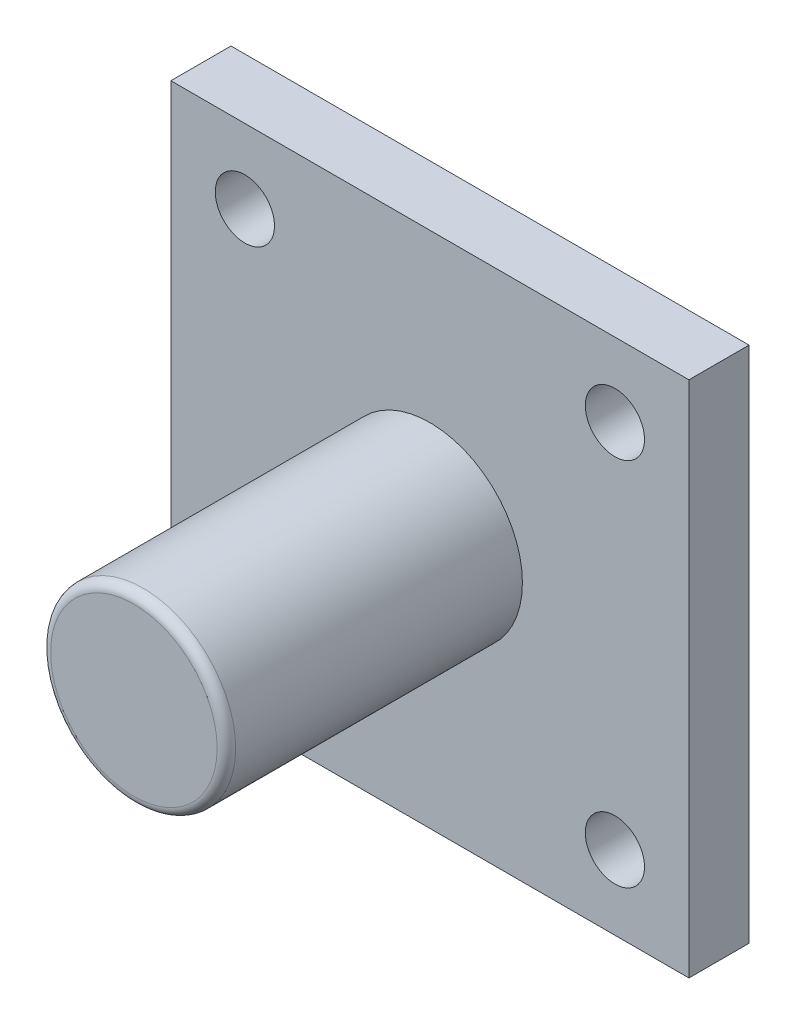
SolidWorks part; units mm, degrees
ref_plane "Front Plane" through (0, 0, 0) normal (0, 0, 1) x (1, 0, 0)
ref_plane "Top Plane" through (0, 0, 0) normal (0, 1, 0) x (1, 0, 0)
ref_plane "Right Plane" through (0, 0, 0) normal (1, 0, 0) x (0, 0, -1)
sketch "Sketch1" plane through (0, 0, 0) normal (0, 0, 1) x (1, 0, 0)
  line L1 (0, 0) -> (28, 0)
  line L2 (0, 0) -> (0, 28)
  line L3 (0, 28) -> (28, 28)
  line L4 (28, 0) -> (28, 28)
  dimension "D1" = 28
  dimension "D2" = 28
extrude "Boss-Extrude1" add sketch "Sketch1" along normal blind 3.25
sketch "Sketch2" plane through (0, 0, 3.25) normal (0, 0, 1) x (1, 0, 0)
  line L0 (14, 28) -> (14, 0) construction
  line L1 (28, 28) -> (0, 28) construction
  line L2 (0, 0) -> (28, 0) construction
  circle A0 centre (14, 14) radius 5
  dimension "D1" = 10
extrude "Boss-Extrude2" add sketch "Sketch2" along normal blind 16
sketch "Sketch3" plane through (0, 0, 0) normal (0, 0, -1) x (-1, 0, 0)
  line L0 (-14, 28) -> (-14, 0) construction
  line L1 (-28, 28) -> (0, 28) construction
  line L2 (0, 0) -> (-28, 0) construction
  circle A0 centre (-24, 24) radius 1.6
  circle A1 centre (-4, 24) radius 1.6
  circle A2 centre (-4, 4) radius 1.6
  circle A3 centre (-24, 4) radius 1.6
  point P8 (-14, 14)
  dimension "D5" = 3.2
  dimension "D6" = 3.2
  dimension "D7" = 3.2
  dimension "D8" = 3.2
  dimension "D1" = 20
  dimension "D2" = 20
  dimension "D3" = 10
  dimension "D4" = 10
extrude "Cut-Extrude1" cut sketch "Sketch3" against normal through all
fillet "Fillet1" radius 0.5 1 edges at (19, 14, 19.25)
sketch "Sketch4" plane through (0, 0, 0) normal (0, 0, -1) x (-1, 0, 0)
  line L0 (-14, 28) -> (-14, 0) construction
  line L1 (-20.5, 25.5) -> (-7.5, 25.5)
  line L2 (-20.5, 25.5) -> (-20.5, 23)
  line L3 (-20.5, 23) -> (-7.5, 23)
  line L4 (-7.5, 25.5) -> (-7.5, 23)
  line L5 (-28, 28) -> (0, 28) construction
  line L6 (0, 0) -> (-28, 0) construction
  line L7 (0, 14) -> (-28, 14) construction
  line L8 (0, 28) -> (0, 0) construction
  line L9 (-28, 0) -> (-28, 28) construction
  line L11 (-5, 20.5) -> (-2.5, 20.5)
  line L12 (-5, 20.5) -> (-5, 7.5)
  line L13 (-5, 7.5) -> (-2.5, 7.5)
  line L14 (-2.5, 20.5) -> (-2.5, 7.5)
  line L15 (-7.5, 5) -> (-20.5, 5)
  line L16 (-7.5, 5) -> (-7.5, 2.5)
  line L17 (-7.5, 2.5) -> (-20.5, 2.5)
  line L18 (-20.5, 5) -> (-20.5, 2.5)
  line L19 (-23, 7.5) -> (-25.5, 7.5)
  line L20 (-23, 7.5) -> (-23, 20.5)
  line L21 (-23, 20.5) -> (-25.5, 20.5)
  line L22 (-25.5, 7.5) -> (-25.5, 20.5)
  dimension "D1" = 13
  dimension "D2" = 6.5
  dimension "D3" = 2.5
  dimension "D4" = 2.5
  dimension "D5" = 2.5
  dimension "D6" = 2.5
  dimension "D7" = 13
  dimension "D8" = 6.5
  dimension "D9" = 2.5
  dimension "D10" = 2.5
  dimension "D11" = 13
  dimension "D12" = 6.5
  dimension "D13" = 2.5
  dimension "D14" = 2.5
  dimension "D15" = 13
  dimension "D16" = 6.5
extrude "Boss-Extrude3" add sketch "Sketch4" along normal blind 0.5
